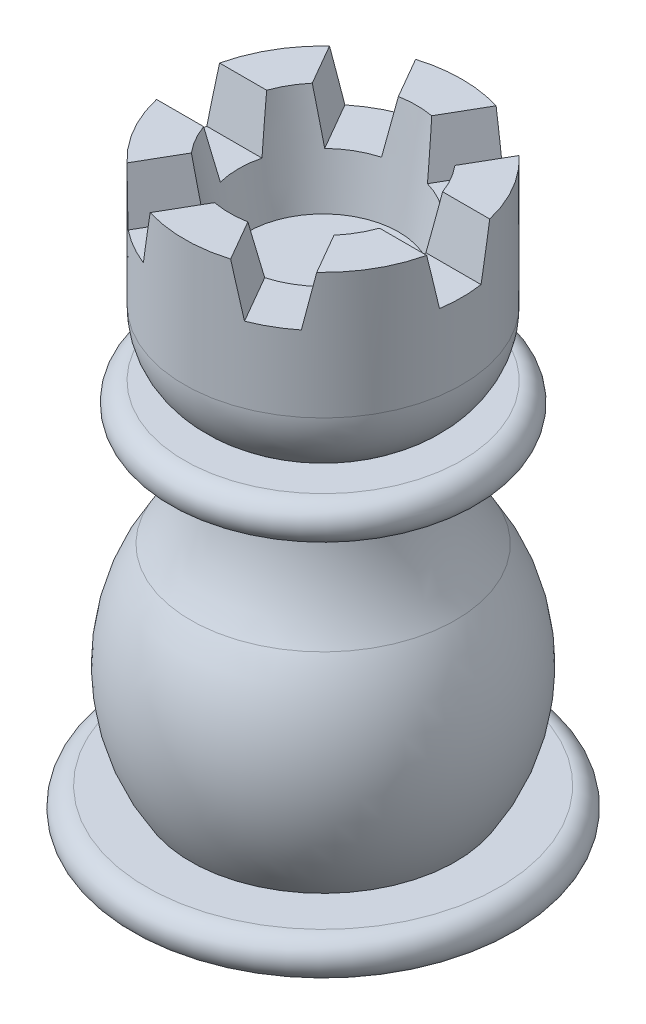
SolidWorks part; units mm, degrees
material "ABS"
ref_plane "Front Plane" through (0, 0, 0) normal (0, 0, 1) x (1, 0, 0)
ref_plane "Top Plane" through (0, 0, 0) normal (0, 1, 0) x (1, 0, 0)
ref_plane "Right Plane" through (0, 0, 0) normal (1, 0, 0) x (0, 0, -1)
sketch "Sketch1" plane through (0, 0, 0) normal (1, 0, 0) x (0, 0, -1)
  line L7 (6, 38) -> (0, 38)
  line L8 (0, 0) -> (0, 38)
  line L9 (0, 0) -> (14, 0)
  line L10 (14, 3) -> (10.5, 3)
  line L11 (8, 27.8038) -> (11, 27.8038)
  line L12 (11, 30.8038) -> (8, 30.8038)
  line L15 (7.4106, 46) -> (6, 38)
  line L16 (11, 36) -> (11, 46)
  line L17 (11, 46) -> (7.4106, 46)
  arc A0 (14, 0) -> (14, 3) centre (14, 1.5) ccw
  arc A1 (10.5, 3) -> (10.4999, 19.5833) centre (-2, 11.2916) ccw
  arc A2 (10.4999, 19.5833) -> (8, 27.8038) centre (22.9998, 27.8749) cw
  arc A5 (11, 27.8038) -> (11, 30.8038) centre (11, 29.3038) ccw
  arc A8 (8, 30.8038) -> (11, 36) centre (5, 36) ccw
  point P13 (0, 0)
  point P17 (8, 30.6703)
  point P18 (8, 26.9728)
  point P19 (0, 0)
  point P22 (11, 37.6303)
  point P23 (0, 0)
  point P24 (0, 0)
  point P27 (11, 34.7277)
  point P28 (11, 36)
  point P29 (11, 35.1214)
  point P30 (8, 27.8038)
  point P31 (6, 27.8038)
  dimension "D2" = 80
  dimension "D4" = 8
  dimension "D5" = 2
  dimension "D9" = 1.5
  dimension "D10" = 11
  dimension "D13" = 15
  dimension "D16" = 14
  dimension "D11" = 8
  dimension "D8" = 6
  dimension "D14" = 2
  dimension "D15" = 15
  dimension "D17" = 1.5
  dimension "D18" = 10.5
  dimension "D3" = 46
  dimension "D6" = 8
  dimension "D7" = 11
  dimension "D12" = 6
revolve "Revolve1" add sketch "Sketch1" angle 360 about L8
sketch "Sketch3" plane through (0, 0, 0) normal (1, 0, 0) x (0, 0, -1)
  line L0 (0, 46) -> (0, 42) construction
  line L1 (7.4106, 46) -> (-7.4106, 46) construction
  line L2 (-2.5, 46) -> (2.5, 46)
  line L3 (2.5, 46) -> (1.6498, 42)
  line L4 (1.6498, 42) -> (-1.6498, 42)
  line L5 (-1.6498, 42) -> (-2.5, 46)
  point P7 (0, 42)
  point P10 (0, 46)
  dimension "D1" = 4
  dimension "D2" = 5
  dimension "D3" = 24
extrude "Cut-Extrude2" cut sketch "Sketch3" against normal through all both and the other way through all
pattern_circular "CirPattern2" count 3 over 360 about axis through (0, 0, 0) along (0, 1, 0) of "Cut-Extrude2"
